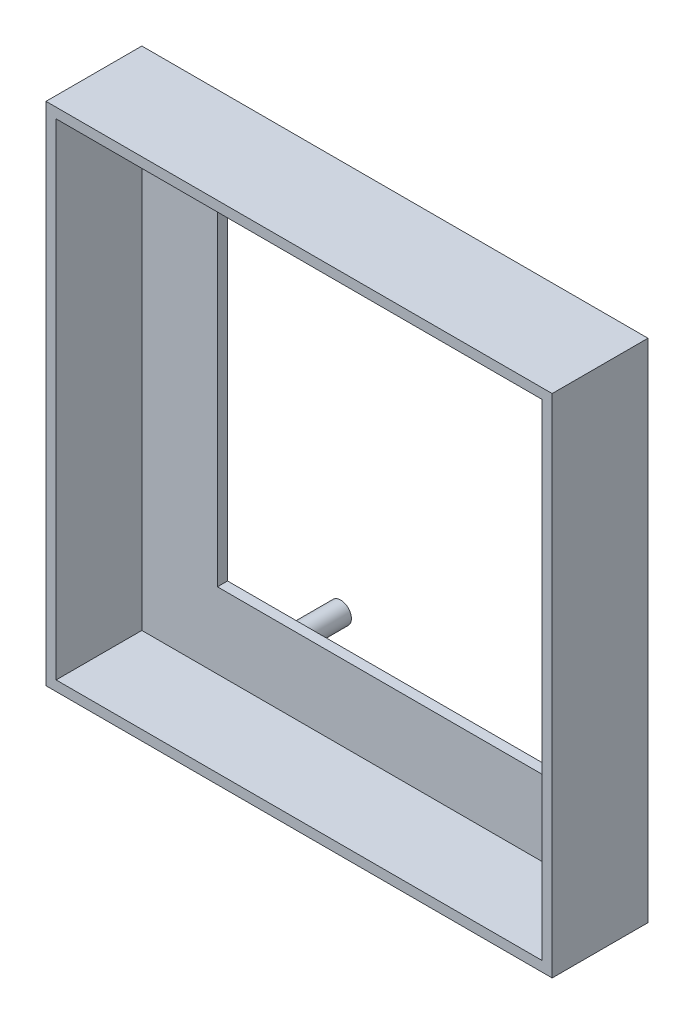
SolidWorks part; units mm, degrees
ref_plane "Alzado" through (0, 0, 0) normal (0, 0, 1) x (1, 0, 0)
ref_plane "Planta" through (0, 0, 0) normal (0, 1, 0) x (1, 0, 0)
ref_plane "Vista lateral" through (0, 0, 0) normal (1, 0, 0) x (0, 0, -1)
sketch "Croquis2" plane through (0, 0, 0) normal (0, 0, 1) x (1, 0, 0)
  line L0 (49.6, 49.6) -> (-49.6, 49.6)
  line L1 (75, -75) -> (-75, -75)
  line L2 (75, -75) -> (75, 75)
  line L3 (75, 75) -> (-75, 75)
  line L4 (-75, -75) -> (-75, 75)
  line L5 (75, -75) -> (-75, 75) construction
  line L6 (75, 75) -> (-75, -75) construction
  line L7 (-49.6, -49.6) -> (-49.6, 49.6)
  line L8 (49.6, -49.6) -> (-49.6, -49.6)
  line L9 (49.6, -49.6) -> (49.6, 49.6)
  point P0 (0, 0)
  dimension "D1" = 150
  dimension "D2" = 150
  dimension "D3" = 25.4
extrude "Saliente-Extruir1" add sketch "Croquis2" along normal blind 3
sketch "Croquis5" plane through (0, 0, 3) normal (0, 0, 1) x (1, 0, 0)
  line L1 (75, -75) -> (-75, -75)
  line L2 (75, -75) -> (75, 75)
  line L3 (75, 75) -> (-75, 75)
  line L4 (-75, -75) -> (-75, 75)
  line L5 (75, -75) -> (-75, 75) construction
  line L6 (75, 75) -> (-75, -75) construction
  line L7 (72, -72) -> (-72, -72)
  line L8 (72, -72) -> (72, 72)
  line L9 (72, 72) -> (-72, 72)
  line L10 (-72, -72) -> (-72, 72)
  line L11 (72, -72) -> (-72, 72) construction
  line L12 (72, 72) -> (-72, -72) construction
  point P0 (0, 0)
  point P7 (0, 0)
  dimension "D1" = 3
  dimension "D2" = 3
extrude "Saliente-Extruir2" add sketch "Croquis5" along normal blind 25.4
sketch "Croquis6" plane through (0, 0, 0) normal (0, 0, -1) x (-1, 0, 0)
  line L0 (75, -55.9) -> (31.07, -55.9) construction
  line L1 (75, 75) -> (75, -75) construction
  line L2 (49.6, -49.6) -> (-49.6, -49.6) construction
  circle A0 centre (31.07, -55.9) radius 3.175
  dimension "D3" = 6.35
  dimension "D1" = 43.93
  dimension "D2" = 6.3
extrude "Saliente-Extruir3" add sketch "Croquis6" along normal blind 15
